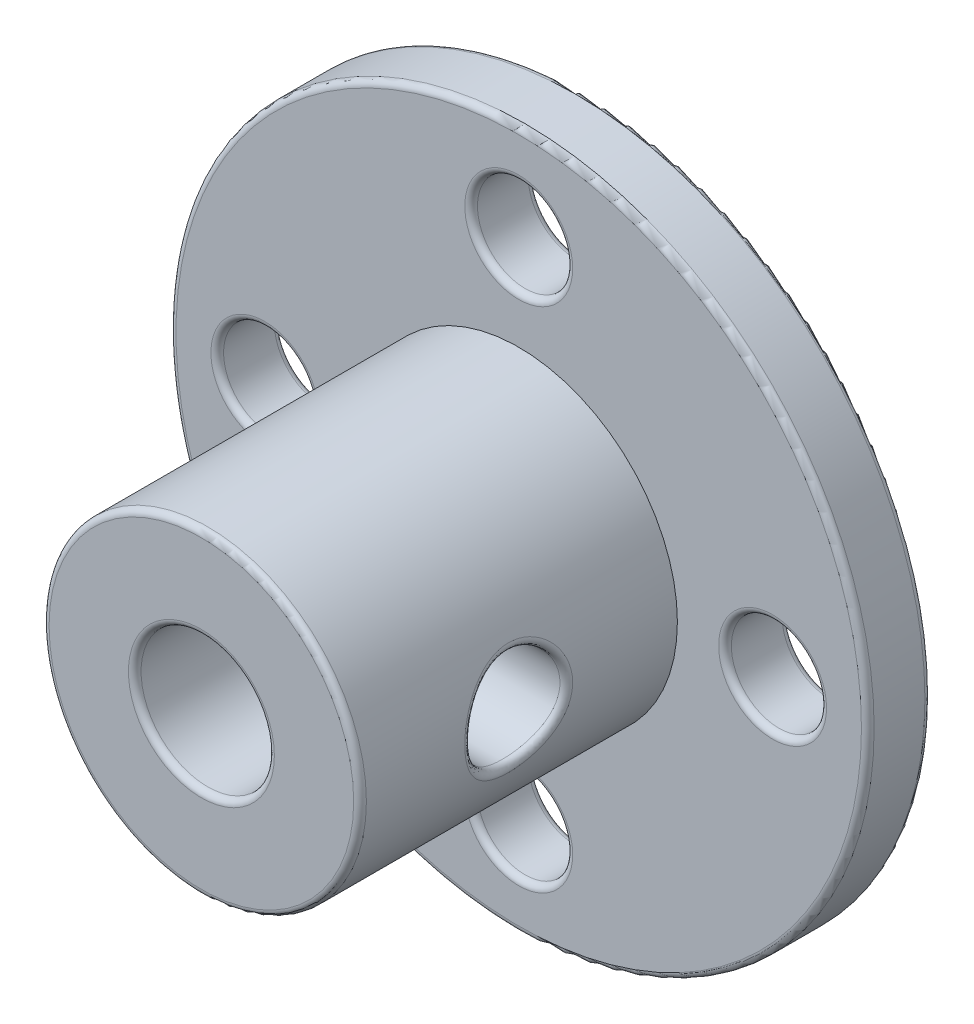
SolidWorks part; units mm, degrees
ref_plane "Front Plane" through (0, 0, 0) normal (0, 0, 1) x (1, 0, 0)
ref_plane "Top Plane" through (0, 0, 0) normal (0, 1, 0) x (1, 0, 0)
ref_plane "Right Plane" through (0, 0, 0) normal (1, 0, 0) x (0, 0, -1)
sketch "Sketch1" plane through (0, 0, 0) normal (0, 0, 1) x (1, 0, 0)
  circle A0 centre (0, 0) radius 11
  dimension "D1" = 22
extrude "Boss-Extrude1" add sketch "Sketch1" along normal blind 2
sketch "Sketch2" plane through (0, 0, 0) normal (0, 0, 1) x (1, 0, 0)
  circle A0 centre (0, 0) radius 5
  dimension "D1" = 10
extrude "Boss-Extrude2" add sketch "Sketch2" along normal blind 10 from surface at 2 starting at face at (11, 0, 2)
sketch "Sketch3" plane through (0, 0, 0) normal (0, 0, 1) x (1, 0, 0)
  circle A0 centre (0, 0) radius 2.1
  dimension "D1" = 4.2
extrude "Cut-Extrude1" cut sketch "Sketch3" along normal through all
sketch "Sketch5" plane through (0, 0, 0) normal (0, 0, 1) x (1, 0, 0)
  line L0 (0, -6.6) -> (0, 6.6) construction
  line L1 (6.6, 0) -> (-6.6, 0) construction
  circle A0 centre (0, 8) radius 1.5
  circle A1 centre (8, 0) radius 1.5
  circle A2 centre (0, -8) radius 1.5
  circle A3 centre (-8, 0) radius 1.5
  dimension "D2" = 3
  dimension "D1" = 8
  dimension "D3" = 8
  dimension "D4" = 8
  dimension "D5" = 8
extrude "Cut-Extrude2" cut sketch "Sketch5" along normal through all
sketch "Sketch6" plane through (0, 0, 0) normal (1, 0, 0) x (0, 0, -1)
  line L0 (6.6, 0) -> (-6.6, 0) construction
  line L1 (0, 12.1) -> (0, -12.1) construction
  circle A0 centre (-7, 0) radius 1.5
  dimension "D1" = 3
  dimension "D2" = 7
extrude "Cut-Extrude3" cut sketch "Sketch6" against normal through all both and the other way through all
fillet "Fillet1" radius 0.2 15 edges at (1.5, -8, 0) (-6.5, 0, 0) (2.1, 0, 0) (1.5, 8, 0) (9.5, 0, 0) (11, 0, 0) (11, 0, 2) (1.5, -8, 2) (-6.5, 0, 2) (1.5, 8, 2) (9.5, 0, 2) (2.1, 0, 12) (5, 0, 12) (-4.9926, 0.2714, 5.5248) (4.9926, 0.2714, 8.4752)
